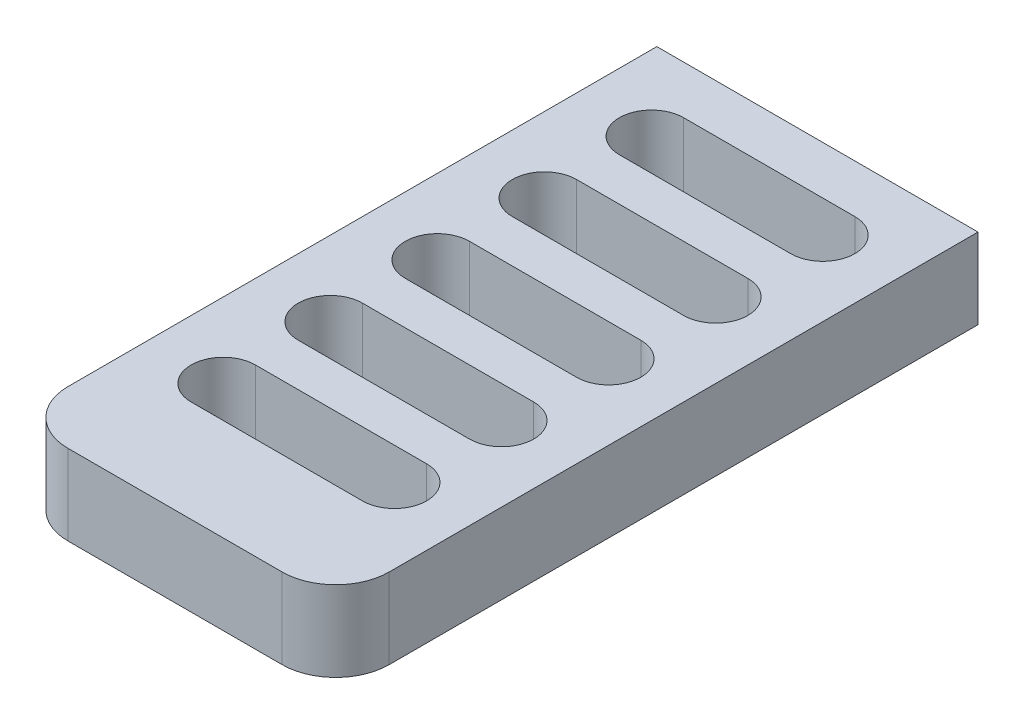
SolidWorks part; units mm, degrees
ref_plane "Спереди" through (0, 0, 0) normal (0, 0, 1) x (1, 0, 0)
ref_plane "Сверху" through (0, 0, 0) normal (0, 1, 0) x (1, 0, 0)
ref_plane "Справа" through (0, 0, 0) normal (1, 0, 0) x (0, 0, -1)
sketch "Эскиз1" plane through (0, 0, 0) normal (0, 1, 0) x (1, 0, 0)
  line L0 (14, 105) -> (46, 105) construction
  line L1 (10, 0) -> (50, 0)
  line L2 (0, 10) -> (0, 120)
  line L3 (0, 120) -> (60, 120)
  line L4 (60, 10) -> (60, 120)
  line L5 (14, 111) -> (46, 111)
  line L6 (14, 99) -> (46, 99)
  line L7 (14, 85) -> (46, 85) construction
  line L8 (14, 91) -> (46, 91)
  line L9 (14, 79) -> (46, 79)
  line L10 (14, 65) -> (46, 65) construction
  line L11 (14, 71) -> (46, 71)
  line L12 (14, 59) -> (46, 59)
  line L13 (14, 45) -> (46, 45) construction
  line L14 (14, 51) -> (46, 51)
  line L15 (14, 39) -> (46, 39)
  line L16 (14, 25) -> (46, 25) construction
  line L17 (14, 31) -> (46, 31)
  line L18 (14, 19) -> (46, 19)
  arc A0 (14, 111) -> (14, 99) centre (14, 105) ccw
  arc A1 (46, 99) -> (46, 111) centre (46, 105) ccw
  arc A2 (14, 91) -> (14, 79) centre (14, 85) ccw
  arc A3 (46, 79) -> (46, 91) centre (46, 85) ccw
  arc A4 (14, 71) -> (14, 59) centre (14, 65) ccw
  arc A5 (46, 59) -> (46, 71) centre (46, 65) ccw
  arc A6 (14, 51) -> (14, 39) centre (14, 45) ccw
  arc A7 (46, 39) -> (46, 51) centre (46, 45) ccw
  arc A8 (14, 31) -> (14, 19) centre (14, 25) ccw
  arc A9 (46, 19) -> (46, 31) centre (46, 25) ccw
  arc A10 (50, 0) -> (60, 10) centre (50, 10) ccw
  arc A11 (10, 0) -> (0, 10) centre (10, 10) cw
  point P7 (30, 105)
  point P14 (30, 85)
  point P21 (30, 65)
  point P28 (30, 45)
  point P35 (30, 25)
  point P44 (0, 0)
  dimension "D3" = 10
  dimension "D1" = 60
  dimension "D2" = 120
extrude "Бобышка-Вытянуть1" add sketch "Эскиз1" along normal blind 15
